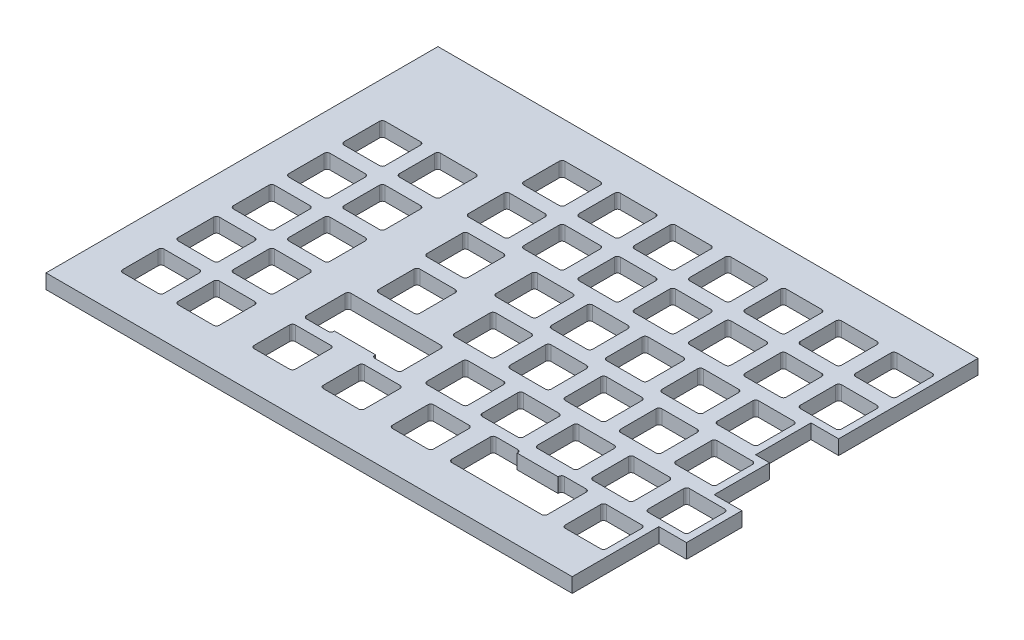
SolidWorks part; units mm, degrees
ref_plane "Front Plane" through (0, 0, 0) normal (0, 0, 1) x (1, 0, 0)
ref_plane "Top Plane" through (0, 0, 0) normal (0, 1, 0) x (1, 0, 0)
ref_plane "Right Plane" through (0, 0, 0) normal (1, 0, 0) x (0, 0, -1)
sketch "Sketch1" plane through (0, 0, 0) normal (0, 1, 0) x (1, 0, 0)
  line L0 (0, 0) -> (0, 135)
  line L1 (0, 135) -> (186, 135)
  line L2 (186, 135) -> (186, 87)
  line L3 (186, 87) -> (176.475, 87)
  line L4 (176.475, 87) -> (176.475, 67.95)
  line L5 (176.475, 67.95) -> (181.2375, 67.95)
  line L6 (181.2375, 67.95) -> (181.2375, 48.9)
  line L7 (181.2375, 48.9) -> (190.7625, 48.9)
  line L8 (190.7625, 48.9) -> (190.7625, 29.85)
  line L9 (190.7625, 29.85) -> (181.2375, 29.85)
  line L10 (181.2375, 29.85) -> (181.2375, 0)
  line L11 (181.2375, 0) -> (0, 0)
  dimension "D1" = 135
  dimension "D2" = 186
  dimension "D3" = 48
  dimension "D4" = 4.7625
  dimension "D5" = 9.525
  dimension "D6" = 19.05
extrude "Plate Frame" add sketch "Sketch1" along normal blind 5
sketch "Sketch4" plane through (0, 5, 0) normal (0, 1, 0) x (1, 0, 0)
  line L0 (19.3125, 96.525) -> (38.3625, 96.525) construction
  line L1 (38.3625, 96.525) -> (38.3625, 77.475) construction
  line L2 (38.3625, 77.475) -> (38.3625, 58.425) construction
  line L3 (38.3625, 58.425) -> (38.3625, 39.375) construction
  line L4 (38.3625, 39.375) -> (38.3625, 20.325) construction
  line L5 (38.3625, 20.325) -> (19.3125, 20.325) construction
  line L6 (19.3125, 20.325) -> (19.3125, 39.375) construction
  line L7 (19.3125, 39.375) -> (19.3125, 58.425) construction
  line L8 (19.3125, 58.425) -> (19.3125, 77.475) construction
  line L9 (19.3125, 77.475) -> (19.3125, 96.525) construction
  line L10 (19.3125, 77.475) -> (38.3625, 77.475) construction
  line L11 (19.3125, 58.425) -> (38.3625, 58.425) construction
  line L12 (19.3125, 39.375) -> (38.3625, 39.375) construction
  line L13 (62.175, 115.575) -> (62.175, 96.525) construction
  line L14 (62.175, 96.525) -> (81.225, 96.525) construction
  line L15 (81.225, 96.525) -> (81.225, 115.575) construction
  line L16 (81.225, 115.575) -> (100.275, 115.575) construction
  line L17 (100.275, 115.575) -> (119.325, 115.575) construction
  line L18 (119.325, 115.575) -> (138.375, 115.575) construction
  line L19 (138.375, 115.575) -> (157.425, 115.575) construction
  line L20 (157.425, 115.575) -> (176.475, 115.575) construction
  line L21 (176.475, 115.575) -> (176.475, 96.525) construction
  line L22 (176.475, 96.525) -> (157.425, 96.525) construction
  line L23 (157.425, 96.525) -> (138.375, 96.525) construction
  line L24 (138.375, 96.525) -> (119.325, 96.525) construction
  line L25 (119.325, 96.525) -> (100.275, 96.525) construction
  line L26 (100.275, 96.525) -> (81.225, 96.525) construction
  line L27 (62.175, 115.575) -> (81.225, 115.575) construction
  line L28 (100.275, 115.575) -> (100.275, 96.525) construction
  line L29 (119.325, 96.525) -> (119.325, 115.575) construction
  line L30 (138.375, 115.575) -> (138.375, 96.525) construction
  line L31 (157.425, 96.525) -> (157.425, 115.575) construction
  line L32 (66.9375, 77.475) -> (90.75, 77.475) construction
  line L33 (90.75, 77.475) -> (109.8, 77.475) construction
  line L34 (109.8, 77.475) -> (128.85, 77.475) construction
  line L35 (128.85, 77.475) -> (147.9, 77.475) construction
  line L36 (147.9, 77.475) -> (166.95, 77.475) construction
  line L37 (95.5125, 58.425) -> (114.5625, 58.425) construction
  line L38 (114.5625, 58.425) -> (133.6125, 58.425) construction
  line L39 (133.6125, 58.425) -> (152.6625, 58.425) construction
  line L40 (152.6625, 58.425) -> (171.7125, 58.425) construction
  line L41 (105.0375, 39.375) -> (124.0875, 39.375) construction
  line L42 (124.0875, 39.375) -> (143.1375, 39.375) construction
  line L43 (143.1375, 39.375) -> (162.1875, 39.375) construction
  line L44 (162.1875, 39.375) -> (181.2375, 39.375) construction
  line L45 (176.475, 77.475) -> (166.95, 77.475) construction
  line L46 (176.475, 67.95) -> (176.475, 87) construction
  line L49 (64.5563, 20.325) -> (88.3688, 20.325) construction
  line L50 (88.3688, 20.325) -> (112.1813, 20.325) construction
  line L51 (69.3188, 58.425) -> (95.5125, 58.425) construction
  line L52 (112.1813, 20.325) -> (171.7125, 20.325) construction
  point P0 (19.3125, 20.325)
  point P1 (38.3625, 20.325)
  point P2 (38.3625, 39.375)
  point P3 (19.3125, 39.375)
  point P4 (19.3125, 58.425)
  point P5 (38.3625, 58.425)
  point P6 (38.3625, 77.475)
  point P7 (19.3125, 77.475)
  point P8 (19.3125, 96.525)
  point P9 (38.3625, 96.525)
  point P12 (62.175, 115.575)
  point P21 (62.175, 96.525)
  point P22 (81.225, 96.525)
  point P23 (81.225, 115.575)
  point P24 (100.275, 115.575)
  point P25 (100.275, 96.525)
  point P26 (119.325, 96.525)
  point P27 (119.325, 115.575)
  point P28 (138.375, 115.575)
  point P29 (138.375, 96.525)
  point P30 (157.425, 96.525)
  point P31 (157.425, 115.575)
  point P32 (176.475, 115.575)
  point P33 (176.475, 96.525)
  point P44 (90.75, 77.475)
  point P49 (66.9375, 77.475)
  point P50 (109.8, 77.475)
  point P51 (128.85, 77.475)
  point P52 (147.9, 77.475)
  point P53 (166.95, 77.475)
  point P54 (95.5125, 58.425)
  point P55 (114.5625, 58.425)
  point P56 (133.6125, 58.425)
  point P57 (152.6625, 58.425)
  point P58 (171.7125, 58.425)
  point P59 (105.0375, 39.375)
  point P60 (124.0875, 39.375)
  point P61 (143.1375, 39.375)
  point P62 (162.1875, 39.375)
  point P63 (181.2375, 39.375)
  point P81 (88.3688, 20.325)
  point P82 (112.1813, 20.325)
  point P83 (69.3188, 58.425)
  point P90 (171.7125, 20.325)
  point P94 (64.5563, 20.325)
  dimension "D1" = 19.05
  dimension "D2" = 9.525
  dimension "D3" = 23.8125
  dimension "D4" = 23.8125
  dimension "D6" = 9.525
  dimension "D5" = 4.7625
  dimension "D7" = 9.525
  dimension "D8" = 23.8125
  dimension "D9" = 26.1938
  dimension "D10" = 26.1938
  dimension "D11" = 59.5312
sketch "Sketch2" plane through (0, 5, 0) normal (0, 1, 0) x (1, 0, 0)
  line L0 (12.2125, 14.225) -> (12.2125, 26.425)
  line L1 (13.2125, 27.425) -> (25.4125, 27.425)
  line L2 (26.4125, 26.425) -> (26.4125, 14.225)
  line L3 (25.4125, 13.225) -> (13.2125, 13.225)
  line L4 (13.2125, 27.425) -> (25.4125, 13.225) construction
  arc A0 (12.2125, 26.425) -> (13.2125, 27.425) centre (13.2125, 26.425) cw
  arc A1 (25.4125, 27.425) -> (26.4125, 26.425) centre (25.4125, 26.425) cw
  arc A2 (26.4125, 14.225) -> (25.4125, 13.225) centre (25.4125, 14.225) cw
  arc A3 (13.2125, 13.225) -> (12.2125, 14.225) centre (13.2125, 14.225) cw
  point P12 (19.3125, 20.325)
  point P13 (43.3698, 34.5592)
  dimension "D3" = 1
  dimension "D1" = 14.2
extrude "1U" cut sketch "Sketch2" against normal through all
pattern_sketch "Sketch-Pattern1" of "1U" driven by "Sketch4"
sketch "Sketch5" plane through (0, 5, 0) normal (0, 1, 0) x (1, 0, 0)
  line L0 (112.1813, 20.325) -> (171.7125, 20.325) construction
  line L1 (74.0813, 39.375) -> (105.0375, 39.375) construction
  point P0 (74.0813, 39.375)
  point P1 (141.9469, 20.325)
  point P4 (141.9469, 20.325)
  point P5 (0, 0)
  dimension "D1" = 30.9563
sketch "Sketch6" plane through (0, 5, 0) normal (0, 1, 0) x (1, 0, 0)
  line L0 (57.5813, 32.125) -> (57.5813, 45.425)
  line L1 (58.5813, 46.425) -> (89.5813, 46.425)
  line L2 (90.5813, 45.425) -> (90.5813, 32.125)
  line L3 (89.5813, 31.125) -> (82.1313, 31.125)
  line L5 (66.0313, 31.125) -> (58.5813, 31.125)
  line L6 (67.0313, 32.125) -> (67.0313, 32.325)
  line L7 (67.0313, 32.325) -> (81.1313, 32.325)
  line L8 (81.1313, 32.325) -> (81.1313, 32.125)
  line L9 (67.0313, 32.325) -> (81.1313, 46.425) construction
  arc A0 (57.5813, 45.425) -> (58.5813, 46.425) centre (58.5813, 45.425) cw
  arc A1 (89.5813, 46.425) -> (90.5813, 45.425) centre (89.5813, 45.425) cw
  arc A2 (90.5813, 32.125) -> (89.5813, 31.125) centre (89.5813, 32.125) cw
  arc A3 (82.1313, 31.125) -> (81.1313, 32.125) centre (82.1313, 32.125) cw
  arc A4 (67.0313, 32.125) -> (66.0313, 31.125) centre (66.0313, 32.125) cw
  arc A5 (58.5813, 31.125) -> (57.5813, 32.125) centre (58.5813, 32.125) cw
  point P18 (0, 0)
  point P23 (74.0813, 39.375)
  dimension "D1" = 1
  dimension "D2" = 14.1
  dimension "D3" = 33
  dimension "D4" = 14.1
  dimension "D5" = 15.3
sketch "Sketch7" plane through (0, 5, 0) normal (0, 1, 0) x (1, 0, 0)
  line L10 (126.4469, 13.275) -> (157.4469, 13.275)
  line L11 (158.4469, 14.275) -> (158.4469, 27.575)
  line L12 (157.4469, 28.575) -> (149.9969, 28.575)
  line L13 (148.9969, 27.575) -> (148.9969, 27.375)
  line L14 (148.9969, 27.375) -> (134.8969, 27.375)
  line L15 (134.8969, 27.375) -> (134.8969, 27.575)
  line L16 (133.8969, 28.575) -> (126.4469, 28.575)
  line L17 (125.4469, 27.575) -> (125.4469, 14.275)
  line L18 (148.9969, 27.375) -> (134.8969, 13.275) construction
  arc A6 (157.4469, 13.275) -> (158.4469, 14.275) centre (157.4469, 14.275) ccw
  arc A7 (158.4469, 27.575) -> (157.4469, 28.575) centre (157.4469, 27.575) ccw
  arc A8 (149.9969, 28.575) -> (148.9969, 27.575) centre (149.9969, 27.575) ccw
  arc A10 (126.4469, 28.575) -> (125.4469, 27.575) centre (126.4469, 27.575) ccw
  arc A11 (125.4469, 14.275) -> (126.4469, 13.275) centre (126.4469, 14.275) ccw
  arc A12 (133.8969, 28.575) -> (134.8969, 27.575) centre (133.8969, 27.575) cw
  point P34 (158.4469, 14.275)
  point P43 (141.9469, 20.325)
  point P46 (207.3571, 20.325)
  dimension "D6" = 1
  dimension "D7" = 14.1
  dimension "D8" = 15.3
  dimension "D9" = 33
  dimension "D10" = 14.1
extrude "Cut-Extrude1" cut sketch "Sketch6" against normal through all
extrude "Cut-Extrude2" cut sketch "Sketch7" against normal through all
equation "\"D2@Sketch4\"=19.05/2"
equation "\"D3@Sketch4\"=19.05/2 + (19.05*1.5)/2"
equation "\"D4@Sketch4\"=19.05/2 + 19.05*.25 + 19.05/2"
equation "\"D6@Sketch4\"=19.05/2"
equation "\"D5@Sketch4\"=19.05/4"
equation "\"D7@Sketch4\"=19.05/2"
equation "\"D5@Sketch1\"=19.05/2"
equation "\"D4@Sketch1\"=19.05/4"
equation "\"D8@Sketch4\"=19.05*1.25"
equation "\"D9@Sketch4\"=19.05/2 + 19.05*1.75/2"
equation "\"D10@Sketch4\"=19.05/2 + 19.05*.25 + 19.05*1.25/2"
equation "\"D11@Sketch4\"=19.05*1.25/2 + 19.05*2 + 19.05/2"
equation "\"D1@Sketch5\"=19.05*2.25/2 + 19.05/2"
